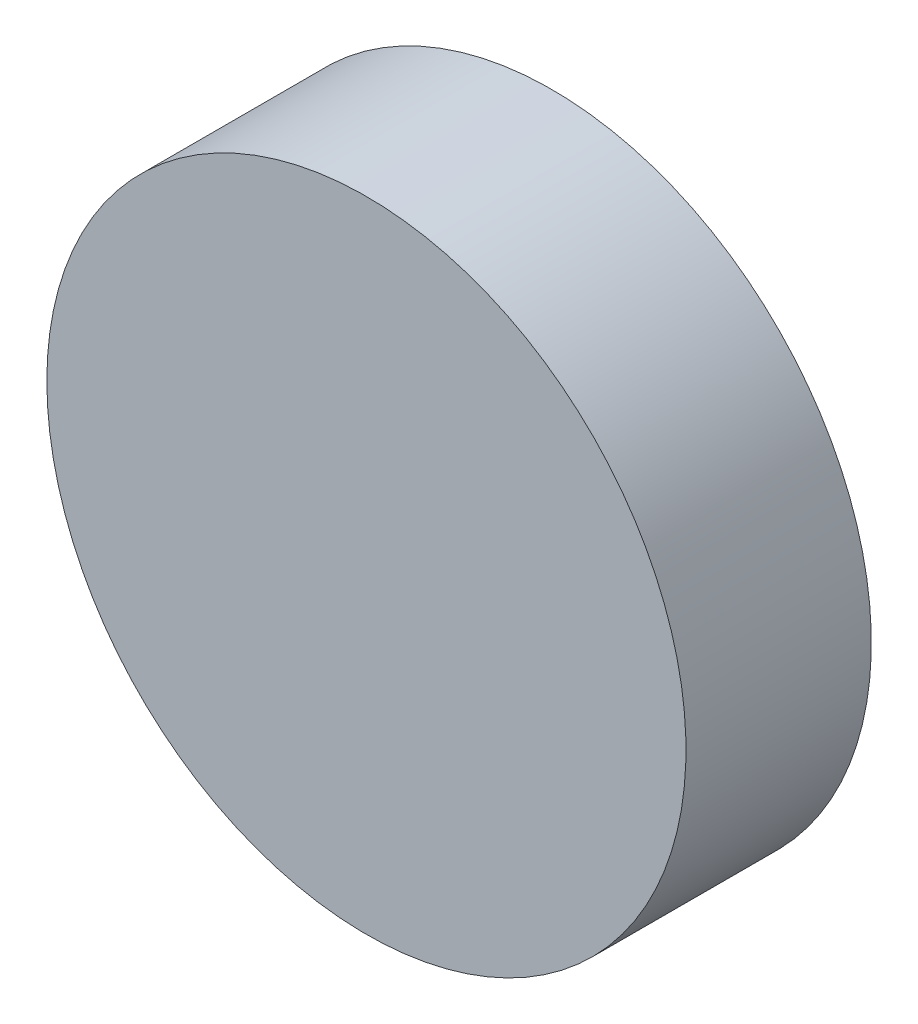
SolidWorks part; units mm, degrees
material "天然橡胶"
ref_plane "前视基准面" through (0, 0, 0) normal (0, 0, 1) x (1, 0, 0)
ref_plane "上视基准面" through (0, 0, 0) normal (0, 1, 0) x (1, 0, 0)
ref_plane "右视基准面" through (0, 0, 0) normal (1, 0, 0) x (0, 0, -1)
other "Configuration Table"
sketch "草图1" plane through (0, 0, 0) normal (0, 0, 1) x (1, 0, 0)
  circle A0 centre (0, 0) radius 50
  dimension "D1" = 100
extrude "凸台-拉伸1" add sketch "草图1" along normal blind 29
